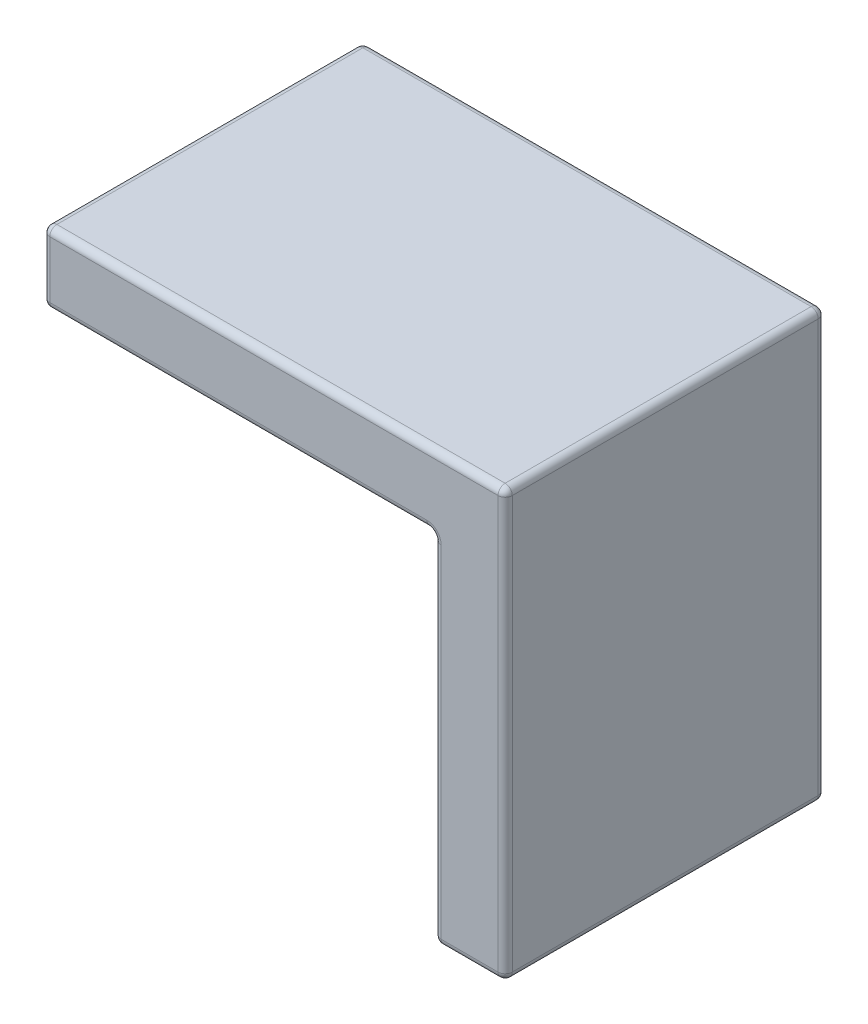
SolidWorks part; units mm, degrees
ref_plane "Ebene vorne" through (0, 0, 0) normal (0, 0, 1) x (1, 0, 0)
ref_plane "Ebene oben" through (0, 0, 0) normal (0, 1, 0) x (1, 0, 0)
ref_plane "Ebene rechts" through (0, 0, 0) normal (1, 0, 0) x (0, 0, -1)
sketch "Skizze1" plane through (0, 0, 0) normal (0, 0, 1) x (1, 0, 0)
  line L1 (-32.5, -30) -> (32.5, -30)
  line L2 (-32.5, -30) -> (-32.5, 30)
  line L3 (-32.5, 30) -> (32.5, 30)
  line L4 (32.5, -30) -> (32.5, 30)
  line L5 (-32.5, -30) -> (32.5, 30) construction
  line L6 (-32.5, 30) -> (32.5, -30) construction
  line L7 (-32.5, 30) -> (32.5, 30)
  line L8 (-32.5, 30) -> (-32.5, 20)
  line L9 (-32.5, 20) -> (32.5, 20)
  line L10 (32.5, 30) -> (32.5, 20)
  line L11 (-32.5, 30) -> (32.5, 20) construction
  line L12 (-32.5, 20) -> (32.5, 30) construction
  line L13 (32.5, 20) -> (22.5, 20)
  line L14 (32.5, 20) -> (32.5, -30)
  line L15 (32.5, -30) -> (22.5, -30)
  line L16 (22.5, 20) -> (22.5, -30)
  line L17 (32.5, 20) -> (22.5, -30) construction
  line L18 (32.5, -30) -> (22.5, 20) construction
  point P0 (0, 0)
  point P8 (0, 25)
  point P11 (27.5, -5)
  dimension "D1" = 65
  dimension "D2" = 60
  dimension "D3" = 10
  dimension "D4" = 10
extrude "Aufsatz-Linear austragen1" add sketch "Skizze1" along normal blind 45 contours L2 L9 L4 L3 | L9 L16 L1 L4
sketch "Skizze2" plane through (0, -30, 0) normal (0, -1, 0) x (1, 0, 0)
  line L0 (22.5, 0) -> (32.5, 0) construction
  circle A0 centre (27.5, 15) radius 2.3
  circle A1 centre (27.5, 35) radius 2.3
  point P6 (0, 0)
  point P7 (27.5, 0)
  dimension "D2" = 4.6
  dimension "D3" = 4.6
  dimension "D1" = 15
  dimension "D4" = 20
extrude "Schnitt-Linear austragen1" cut sketch "Skizze2" against normal blind 10
sketch "Skizze3" plane through (-32.5, 0, 0) normal (-1, 0, 0) x (0, 0, 1)
  circle A0 centre (15, 25) radius 2.3
  circle A1 centre (35, 25) radius 2.3
  dimension "D1" = 4.6
  dimension "D2" = 4.6
extrude "Schnitt-Linear austragen2" cut sketch "Skizze3" against normal blind 10
sketch "Skizze4" plane through (0, 0, 0) normal (0, 0, -1) x (-1, 0, 0)
  circle A0 centre (-17.5, 25) radius 2.15
  circle A1 centre (2.5, 25) radius 2.15
  circle A2 centre (22.5, 25) radius 2.15
  dimension "D1" = 4.3
  dimension "D2" = 4.3
  dimension "D3" = 4.3
extrude "Schnitt-Linear austragen3" cut sketch "Skizze4" against normal blind 10
fillet "Verrundung1" radius 1 25 edges at (-32.5, 25, 45) (-32.5, 25, 37.3) (-32.5, 25, 17.3) (-32.5, 25, 0) (-24.65, 25, 0) (-4.65, 25, 0) (15.35, 25, 0) (0, 30, 45) (-32.5, 30, 22.5) (0, 30, 0) (32.5, 0, 45) (32.5, 30, 22.5) (32.5, 0, 0) (27.5, -30, 45) (32.5, -30, 22.5) (27.5, -30, 0) (27.5, -30, 32.7) (27.5, -30, 12.7) (22.5, -5, 45) (22.5, -30, 22.5) (22.5, -5, 0) (-32.5, 20, 22.5) (-5, 20, 45) (22.5, 20, 22.5) (-5, 20, 0)
